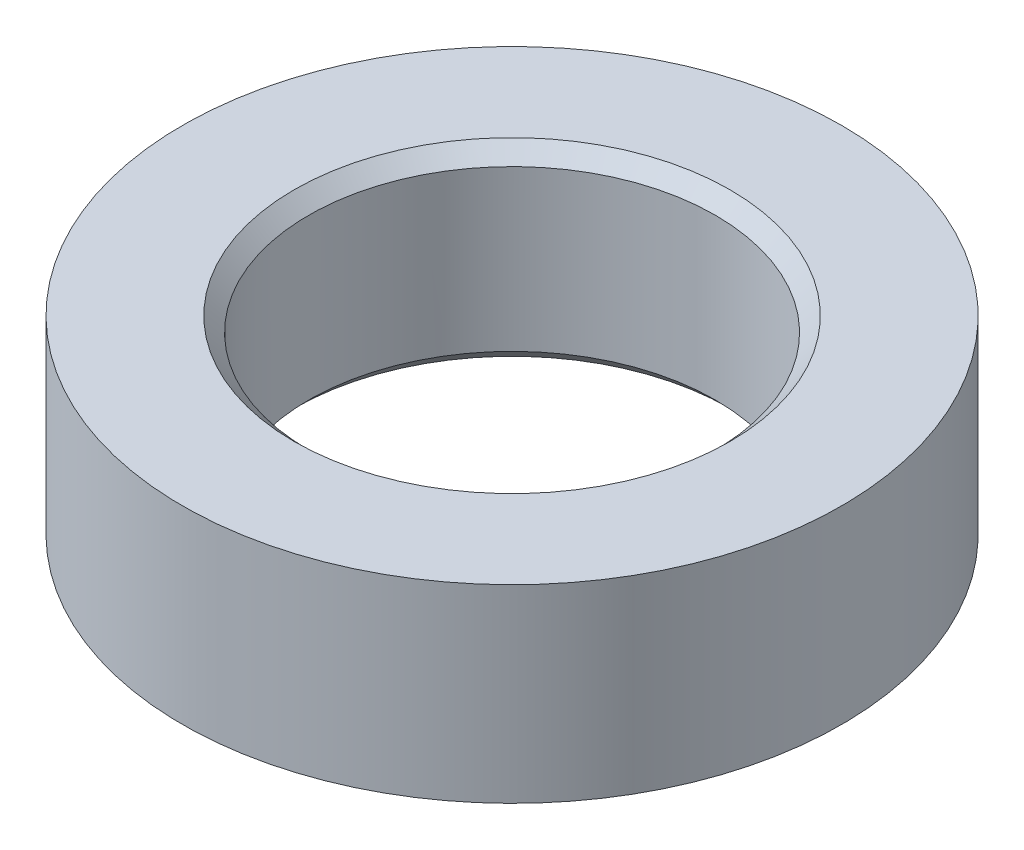
SolidWorks part; units mm, degrees
material "可锻铸铁"
ref_plane "前视基准面" through (0, 0, 0) normal (0, 0, 1) x (1, 0, 0)
ref_plane "上视基准面" through (0, 0, 0) normal (0, 1, 0) x (1, 0, 0)
ref_plane "右视基准面" through (0, 0, 0) normal (1, 0, 0) x (0, 0, -1)
sketch "草图1" plane through (0, 0, 0) normal (0, 1, 0) x (1, 0, 0)
  circle A0 centre (0, 0) radius 11.225
  circle A1 centre (0, 0) radius 6.925
  dimension "D1" = 22.45
  dimension "D2" = 13.85
extrude "凸台-拉伸1" add sketch "草图1" along normal blind 6.45
chamfer "倒角1" distance 0.5 angle 45 2 edges at (0, 0, 6.925) (0, 6.45, 6.925)
